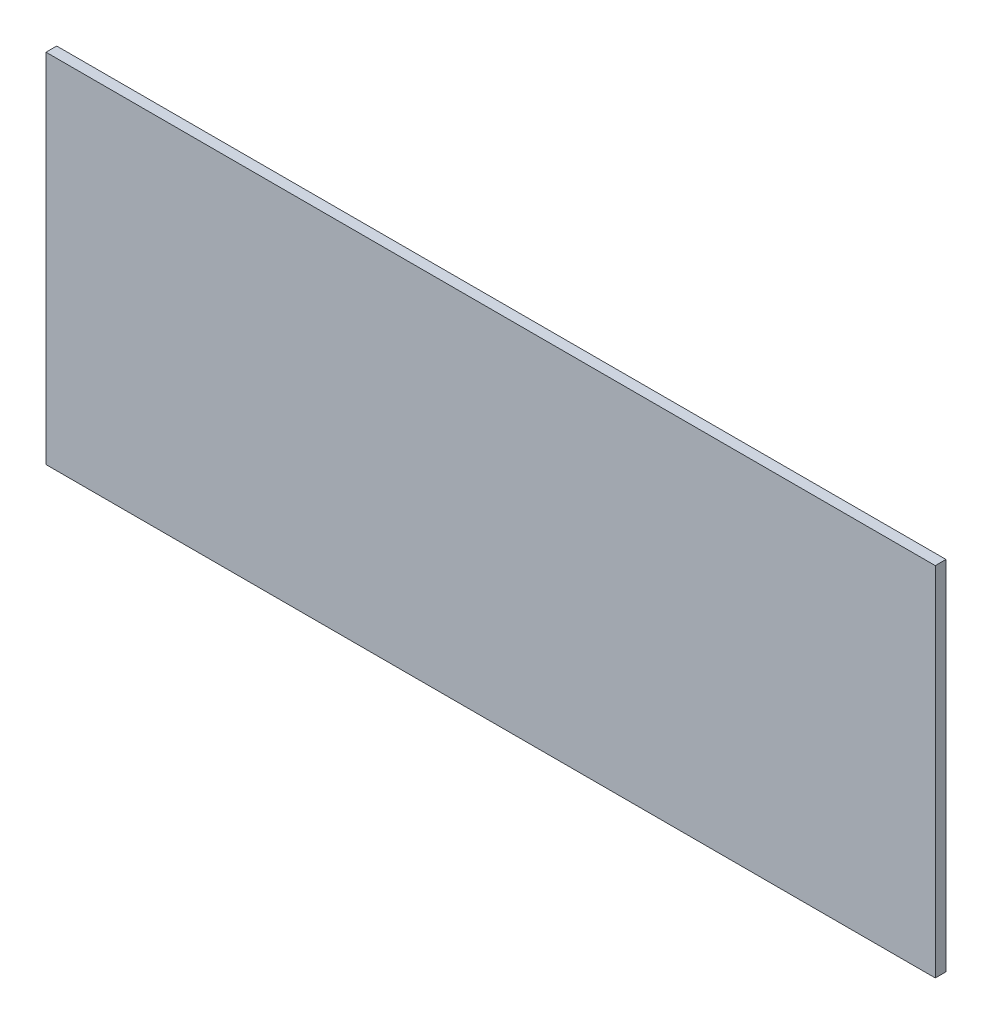
SolidWorks part; units mm, degrees
material "Chapa F.F 1020 - 1,5 mm"
ref_plane "Plano frontal" through (0, 0, 0) normal (0, 0, 1) x (1, 0, 0)
ref_plane "Plano superior" through (0, 0, 0) normal (0, 1, 0) x (1, 0, 0)
ref_plane "Plano direito" through (0, 0, 0) normal (1, 0, 0) x (0, 0, -1)
sketch "Esboço1" plane through (0, 0, 0) normal (0, 0, 1) x (1, 0, 0)
  line L1 (0, 0) -> (124.5, 0)
  line L2 (0, 0) -> (0, 50)
  line L3 (0, 50) -> (124.5, 50)
  line L4 (124.5, 0) -> (124.5, 50)
  dimension "D1" = 124.5
  dimension "D2" = 50
extrude "Ressalto-extrusão1" add sketch "Esboço1" along normal blind 1.5
